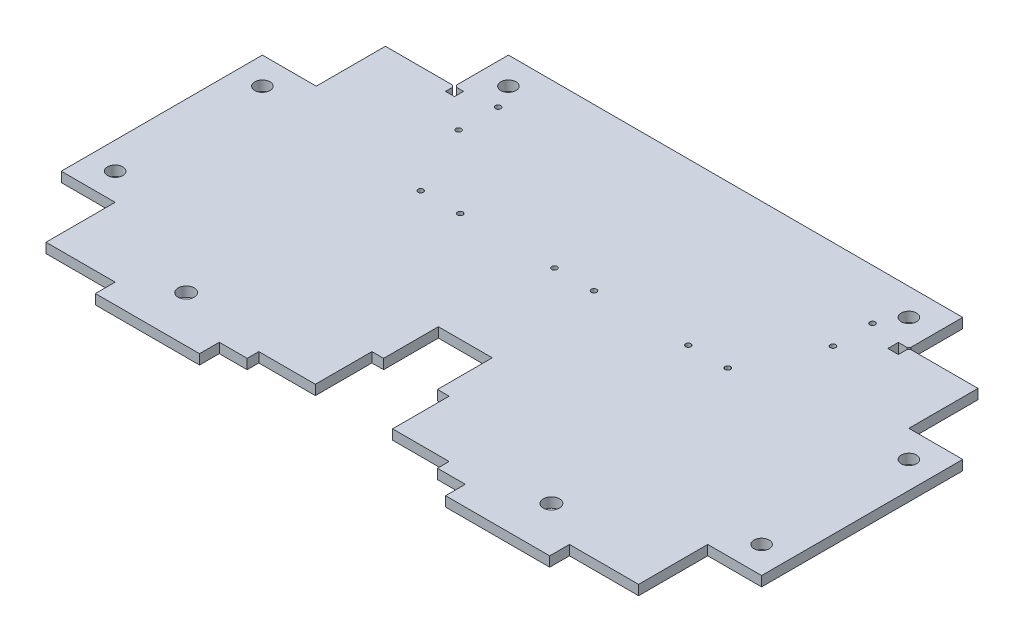
SolidWorks part; units mm, degrees
ref_plane "Alzado" through (0, 0, 0) normal (0, 0, 1) x (1, 0, 0)
ref_plane "Planta" through (0, 0, 0) normal (0, 1, 0) x (1, 0, 0)
ref_plane "Vista lateral" through (0, 0, 0) normal (1, 0, 0) x (0, 0, -1)
sketch "Croquis1" plane through (0, 0, 0) normal (0, 1, 0) x (1, 0, 0)
  line L1 (-195, 115) -> (195, 115)
  line L2 (-195, 115) -> (-195, -115)
  line L3 (-195, -115) -> (195, -115)
  line L4 (195, 115) -> (195, -115)
  line L5 (-195, 115) -> (195, -115) construction
  line L6 (-195, -115) -> (195, 115) construction
  point P0 (0, 0)
extrude "Saliente-Extruir1" add sketch "Croquis1" along normal blind 5.5
sketch "Croquis2" plane through (0, 5.5, 0) normal (0, 1, 0) x (1, 0, 0)
  line L1 (-195, 115) -> (-165, 115)
  line L2 (-195, 115) -> (-195, 85)
  line L3 (-195, 85) -> (-165, 85)
  line L4 (-165, 115) -> (-165, 85)
  line L5 (195, 115) -> (165, 115)
  line L6 (195, 115) -> (195, 85)
  line L7 (195, 85) -> (165, 85)
  line L8 (165, 115) -> (165, 85)
extrude "Cortar-Extruir1" cut sketch "Croquis2" against normal blind 5.5
sketch "Croquis3" plane through (0, 5.5, 0) normal (0, 1, 0) x (1, 0, 0)
  line L1 (-165, 115) -> (-126.5, 115)
  line L2 (-165, 115) -> (-165, 85)
  line L3 (-165, 85) -> (-126.5, 85)
  line L4 (-126.5, 115) -> (-126.5, 85)
  line L5 (165, 115) -> (126.5, 115)
  line L6 (165, 115) -> (165, 85)
  line L7 (165, 85) -> (126.5, 85)
  line L8 (126.5, 115) -> (126.5, 85)
extrude "Cortar-Extruir2" cut sketch "Croquis3" against normal blind 5.5
sketch "Croquis4" plane through (0, 5.5, 0) normal (0, 1, 0) x (1, 0, 0)
  line L1 (-195, 85) -> (-165, 85)
  line L2 (-195, 85) -> (-195, 46.5)
  line L3 (-195, 46.5) -> (-165, 46.5)
  line L4 (-165, 85) -> (-165, 46.5)
  line L5 (195, 85) -> (165, 85)
  line L6 (195, 85) -> (195, 46.5)
  line L7 (195, 46.5) -> (165, 46.5)
  line L8 (165, 85) -> (165, 46.5)
extrude "Cortar-Extruir3" cut sketch "Croquis4" against normal blind 5.5
sketch "Croquis5" plane through (0, 5.5, 0) normal (0, 1, 0) x (1, 0, 0)
  line L1 (-195, -115) -> (-165, -115)
  line L2 (-195, -115) -> (-195, -76.5)
  line L3 (-195, -76.5) -> (-165, -76.5)
  line L4 (-165, -115) -> (-165, -76.5)
  line L5 (195, -115) -> (165, -115)
  line L6 (195, -115) -> (195, -76.5)
  line L7 (195, -76.5) -> (165, -76.5)
  line L8 (165, -115) -> (165, -76.5)
extrude "Cortar-Extruir4" cut sketch "Croquis5" against normal blind 5.5
sketch "Croquis6" plane through (0, 5.5, 0) normal (0, 1, 0) x (1, 0, 0)
  line L0 (-165, -115) -> (165, -115) construction
  line L1 (0, -115) -> (68.5, -115)
  line L2 (0, -115) -> (0, -104)
  line L3 (0, -104) -> (68.5, -104)
  line L4 (68.5, -115) -> (68.5, -104)
extrude "Cortar-Extruir5" cut sketch "Croquis6" against normal blind 5.5
sketch "Croquis7" plane through (0, 5.5, 0) normal (0, 1, 0) x (1, 0, 0)
  line L1 (0, -115) -> (-68.5, -115)
  line L2 (0, -115) -> (0, -104)
  line L3 (0, -104) -> (-68.5, -104)
  line L4 (-68.5, -115) -> (-68.5, -104)
extrude "Cortar-Extruir6" cut sketch "Croquis7" against normal blind 5.5
sketch "Croquis8" plane through (0, 5.5, 0) normal (0, 1, 0) x (1, 0, 0)
  line L0 (68.5, -104) -> (-68.5, -104) construction
  line L1 (-15, -74) -> (15, -74)
  line L2 (-15, -74) -> (-15, -104)
  line L3 (-15, -104) -> (15, -104)
  line L4 (15, -74) -> (15, -104)
  line L5 (-15, -74) -> (15, -104) construction
  line L6 (-15, -104) -> (15, -74) construction
  point P0 (0, -89)
  dimension "D1" = 0
extrude "Cortar-Extruir7" cut sketch "Croquis8" against normal blind 5.5
sketch "Croquis9" plane through (0, 5.5, 0) normal (0, 1, 0) x (1, 0, 0)
  line L1 (-15, -74) -> (15, -74)
  line L2 (-15, -74) -> (-15, -35.5)
  line L3 (-15, -35.5) -> (15, -35.5)
  line L4 (15, -74) -> (15, -35.5)
extrude "Cortar-Extruir8" cut sketch "Croquis9" against normal blind 5.5
sketch "Croquis10" plane through (0, 5.5, 0) normal (0, 1, 0) x (1, 0, 0)
  line L0 (126.5, 115) -> (-126.5, 115) construction
  line L1 (-126.5, 85) -> (-126.5, 115) construction
  line L2 (126.5, 115) -> (126.5, 85) construction
  line L3 (-195, 46.5) -> (-195, -76.5) construction
  line L4 (-195, 46.5) -> (-165, 46.5) construction
  line L5 (-165, -76.5) -> (-195, -76.5) construction
  line L6 (195, -76.5) -> (195, 46.5) construction
  circle A0 centre (-111.5, 100) radius 4.25
  circle A1 centre (111.5, 100) radius 4.25
  circle A2 centre (-180, 31.5) radius 4.25
  circle A3 centre (-180, -61.5) radius 4.25
  circle A4 centre (180, 31.5) radius 4.25
  circle A5 centre (180, -61.5) radius 4.25
  dimension "D1" = 15
  dimension "D2" = 15
  dimension "D4" = 15
  dimension "D6" = 15
  dimension "D7" = 15
  dimension "D3" = 15
  dimension "D5" = 15
extrude "Cortar-Extruir9" cut sketch "Croquis10" against normal blind 5.5
sketch "Croquis11" plane through (0, 5.5, 0) normal (0, 1, 0) x (1, 0, 0)
  line L0 (126.5, 85) -> (127.25, 85)
  line L1 (126.5, 85) -> (165, 85) construction
  line L2 (126.5, 85) -> (126.5, 85.75)
  line L3 (126.5, 115) -> (126.5, 85) construction
  line L4 (126.5, 85) -> (125.75, 85) construction
  line L5 (126.5, 85) -> (126.5, 84.25) construction
  line L6 (126.5, 85.75) -> (125.75, 85)
  line L7 (125.75, 85) -> (126.5, 84.25)
  line L8 (126.5, 84.25) -> (127.25, 85)
extrude "Cortar-Extruir10" cut sketch "Croquis11" against normal blind 5.5
sketch "Croquis12" plane through (0, 5.5, 0) normal (0, 1, 0) x (1, 0, 0)
  line L0 (125.75, 85) -> (125.5732, 85.1768)
  line L1 (125.5732, 85.1768) -> (126.5, 86.1036)
  line L2 (126.5, 115) -> (126.5, 85.75) construction
  line L3 (126.5, 86.1036) -> (127.6036, 85)
  line L4 (127.25, 85) -> (165, 85) construction
  line L5 (127.6036, 85) -> (126.6768, 84.0732)
  line L6 (126.6768, 84.0732) -> (125.75, 85)
extrude "Cortar-Extruir11" cut sketch "Croquis12" against normal blind 5.5
sketch "Croquis13" plane through (0, 5.5, 0) normal (0, 1, 0) x (1, 0, 0)
  line L0 (127.6036, 85) -> (165, 85) construction
  line L1 (120.6422, 85) -> (126.5, 85)
  line L2 (120.6422, 85) -> (120.6422, 79.1422)
  line L3 (120.6422, 79.1422) -> (126.5, 79.1422)
  line L4 (126.5, 85) -> (126.5, 79.1422)
  line L5 (120.6422, 85) -> (126.5, 79.1422) construction
  line L6 (120.6422, 79.1422) -> (126.5, 85) construction
  line L7 (126.5, 115) -> (126.5, 86.1036) construction
  point P0 (123.5711, 82.0711)
  dimension "D1" = 0
  dimension "D2" = 0
extrude "Cortar-Extruir12" cut sketch "Croquis13" against normal blind 5.5
sketch "Croquis14" plane through (0, 5.5, 0) normal (0, 1, 0) x (1, 0, 0)
  line L0 (125.7704, 85.3739) -> (126.8739, 84.2704)
  line L1 (126.5, 86.1036) -> (125.5732, 85.1768) construction
  line L2 (126.6768, 84.0732) -> (127.6036, 85) construction
  line L3 (126.8739, 84.2704) -> (125.9037, 83.3001)
  line L4 (125.9037, 83.3001) -> (124.8001, 84.4037)
  line L5 (124.8001, 84.4037) -> (125.7704, 85.3739)
extrude "Cortar-Extruir13" cut sketch "Croquis14" against normal blind 5.5
sketch "Croquis15" plane through (0, 5.5, 0) normal (0, 1, 0) x (1, 0, 0)
  line L0 (-126.5, 85) -> (-126.5, 86.1)
  line L1 (-126.5, 85) -> (-126.5, 115) construction
  line L2 (-126.5, 85) -> (-127.6, 85)
  line L3 (-165, 85) -> (-126.5, 85) construction
  line L4 (-126.5, 85) -> (-125.4, 85) construction
  line L5 (-126.5, 85) -> (-126.5, 83.9) construction
  line L6 (-127.6, 85) -> (-126.5, 83.9)
  line L7 (-126.5, 83.9) -> (-125.4, 85)
  line L8 (-125.4, 85) -> (-126.5, 86.1)
extrude "Cortar-Extruir14" cut sketch "Croquis15" against normal blind 5.5
sketch "Croquis16" plane through (0, 5.5, 0) normal (0, 1, 0) x (1, 0, 0)
  line L0 (-126.5, 86.1) -> (-126.5, 115) construction
  line L1 (-121.5, 85) -> (-126.5, 85)
  line L2 (-121.5, 85) -> (-121.5, 80)
  line L3 (-121.5, 80) -> (-126.5, 80)
  line L4 (-126.5, 85) -> (-126.5, 80)
  line L5 (-121.5, 85) -> (-126.5, 80) construction
  line L6 (-121.5, 80) -> (-126.5, 85) construction
  line L7 (-165, 85) -> (-127.6, 85) construction
  point P0 (-124, 82.5)
  dimension "D1" = 0
  dimension "D2" = 0
extrude "Cortar-Extruir15" cut sketch "Croquis16" against normal blind 5.5
sketch "Croquis17" plane through (0, 5.5, 0) normal (0, 1, 0) x (1, 0, 0)
  line L0 (-165, -115) -> (-68.5, -115) construction
  line L1 (68.5, -115) -> (165, -115) construction
  line L2 (-195, 46.5) -> (-195, -76.5) construction
  line L3 (195, -76.5) -> (195, 46.5) construction
  circle A0 centre (-101.7, -89.25) radius 4.5
  circle A1 centre (101.7, -89.25) radius 4.5
  dimension "D1" = 25.75
  dimension "D2" = 25.75
  dimension "D3" = 93.3
  dimension "D4" = 93.3
extrude "Cortar-Extruir16" cut sketch "Croquis17" against normal blind 10
sketch "Croquis18" plane through (0, 5.5, 0) normal (0, 1, 0) x (1, 0, 0)
  line L0 (-15, -104) -> (-53, -104)
  line L1 (-15, -104) -> (-68.5, -104) construction
  line L2 (-53, -104) -> (-53, -97.5)
  line L3 (-53, -97.5) -> (-21.5, -97.5)
  line L4 (-15, -104) -> (-15, -66)
  line L5 (-15, -35.5) -> (-15, -104) construction
  line L6 (-15, -66) -> (-21.5, -66)
  line L7 (-21.5, -66) -> (-21.5, -97.5)
  line L8 (15, -66) -> (15, -104)
  line L9 (15, -104) -> (15, -35.5) construction
  line L10 (15, -104) -> (53, -104)
  line L11 (68.5, -104) -> (15, -104) construction
  line L12 (53, -104) -> (53, -97.5)
  line L13 (53, -97.5) -> (21.5, -97.5)
  line L14 (21.5, -97.5) -> (21.5, -66)
  line L15 (21.5, -66) -> (15, -66)
extrude "Cortar-Extruir17" cut sketch "Croquis18" against normal blind 10
sketch "Croquis19" plane through (0, 5.5, 0) normal (0, 1, 0) x (1, 0, 0)
  line L0 (126.5, 115) -> (-126.5, 115) construction
  circle A0 centre (-85.5, 25.15) radius 1.5
  circle A1 centre (-63.5, 25.15) radius 1.5
  circle A2 centre (-11, 25.15) radius 1.5
  circle A3 centre (11, 25.15) radius 1.5
  circle A4 centre (63.5, 25.15) radius 1.5
  circle A5 centre (85.5, 25.15) radius 1.5
  circle A6 centre (-104.25, 87) radius 1.5
  circle A7 centre (-104.25, 65) radius 1.5
  circle A8 centre (104.25, 87) radius 1.5
  circle A9 centre (104.25, 65) radius 1.5
  dimension "D1" = 22
  dimension "D6" = 22
  dimension "D8" = 85.5
  dimension "D9" = 22
  dimension "D11" = 104.25
  dimension "D12" = 104.25
  dimension "D2" = 22
  dimension "D3" = 11
  dimension "D4" = 89.85
  dimension "D5" = 0
  dimension "D7" = 85.5
  dimension "D10" = 28
extrude "Cortar-Extruir19" cut sketch "Croquis19" against normal blind 10
sketch "Croquis20" plane through (0, 5.5, 0) normal (0, 1, 0) x (1, 0, 0)
  line L0 (165, -76.5) -> (165, -115) construction
  line L1 (165, -104) -> (195, -104)
  line L2 (165, -104) -> (165, -65.5)
  line L3 (165, -65.5) -> (195, -65.5)
  line L4 (195, -104) -> (195, -65.5)
  line L5 (68.5, -104) -> (53, -104) construction
  line L6 (-165, -115) -> (-165, -76.5) construction
  line L7 (-165, -104) -> (-195, -104)
  line L8 (-165, -104) -> (-165, -65.5)
  line L9 (-165, -65.5) -> (-195, -65.5)
  line L10 (-195, -104) -> (-195, -65.5)
  line L11 (-195, 46.5) -> (-195, -76.5) construction
  dimension "D1" = 0
  dimension "D2" = 38.5
extrude "Cortar-Extruir20" cut sketch "Croquis20" against normal blind 10
sketch "Croquis21" plane through (0, 5.5, 0) normal (0, 1, 0) x (1, 0, 0)
  line L0 (195, -65.5) -> (181.4361, -65.5) construction
  circle A0 centre (180, -50.5) radius 4.25
  circle A1 centre (-180, -50.5) radius 4.25
  dimension "D1" = 15
extrude "Cortar-Extruir21" cut sketch "Croquis21" against normal blind 10
sketch "Croquis22" plane through (0, 5.5, 0) normal (0, 1, 0) x (1, 0, 0)
  circle A0 centre (-180, -61.5) radius 4.25
  circle A1 centre (180, -61.5) radius 4.25
extrude "Saliente-Extruir2" add sketch "Croquis22" against normal blind 10
sketch "Croquis23" plane through (0, 5.5, 0) normal (0, 1, 0) x (1, 0, 0)
  line L0 (178.5639, -65.5) -> (165, -65.5) construction
  line L1 (176.0077, -65.5) -> (184.2992, -65.5)
  line L2 (176.0077, -65.5) -> (176.0077, -68.4063)
  line L3 (176.0077, -68.4063) -> (184.2992, -68.4063)
  line L4 (184.2992, -65.5) -> (184.2992, -68.4063)
  line L5 (-181.4361, -65.5) -> (-195, -65.5) construction
  line L6 (-185.6646, -65.5) -> (-170.7993, -65.5)
  line L7 (-185.6646, -65.5) -> (-185.6646, -70.0434)
  line L8 (-185.6646, -70.0434) -> (-170.7993, -70.0434)
  line L9 (-170.7993, -65.5) -> (-170.7993, -70.0434)
extrude "Cortar-Extruir22" cut sketch "Croquis23" against normal blind 10
sketch "Croquis24" plane through (0, 5.5, 0) normal (0, 1, 0) x (1, 0, 0)
  line L1 (165, -115) -> (126.5, -115)
  line L2 (165, -115) -> (165, -104)
  line L3 (165, -104) -> (126.5, -104)
  line L4 (126.5, -115) -> (126.5, -104)
extrude "Cortar-Extruir23" cut sketch "Croquis24" against normal blind 10
sketch "Croquis25" plane through (0, 5.5, 0) normal (0, 1, 0) x (1, 0, 0)
  line L1 (-165, -115) -> (-126.5, -115)
  line L2 (-165, -115) -> (-165, -104)
  line L3 (-165, -104) -> (-126.5, -104)
  line L4 (-126.5, -115) -> (-126.5, -104)
extrude "Cortar-Extruir24" cut sketch "Croquis25" against normal blind 10
sketch "Croquis26" plane through (0, 0, 65.5) normal (0, 0, 1) x (1, 0, 0)
  line L1 (-195, 0) -> (208.8945, 0)
  line L2 (-195, 0) -> (-195, -21.3306)
  line L3 (-195, -21.3306) -> (208.8945, -21.3306)
  line L4 (208.8945, 0) -> (208.8945, -21.3306)
extrude "Cortar-Extruir25" cut sketch "Croquis26" against normal blind 10
